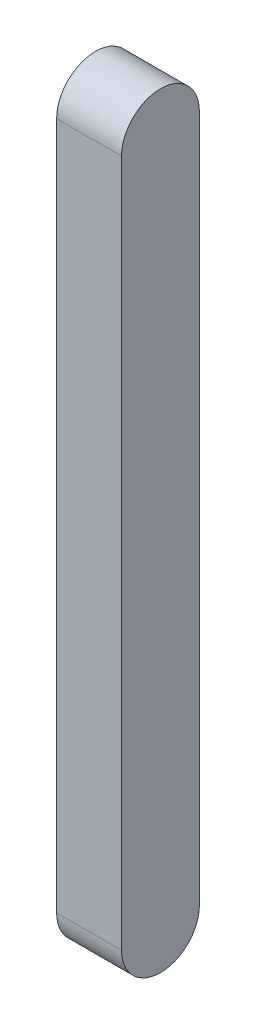
SolidWorks part; units mm, degrees
ref_plane "前视基准面" through (0, 0, 0) normal (0, 0, 1) x (1, 0, 0)
ref_plane "上视基准面" through (0, 0, 0) normal (0, 1, 0) x (1, 0, 0)
ref_plane "右视基准面" through (0, 0, 0) normal (1, 0, 0) x (0, 0, -1)
other "Configuration Table"
sketch "草图1" plane through (0, 0, 0) normal (1, 0, 0) x (0, 0, -1)
  line L0 (0, 0) -> (0, -212) construction
  line L1 (12, 0) -> (12, -212)
  line L2 (-12, 0) -> (-12, -212)
  arc A0 (12, 0) -> (-12, 0) centre (0, 0) ccw
  arc A1 (-12, -212) -> (12, -212) centre (0, -212) ccw
  point P3 (0, -106)
  dimension "D2" = 12
  dimension "D1" = 212
extrude "凸台-拉伸1" add sketch "草图1" along normal blind 20
